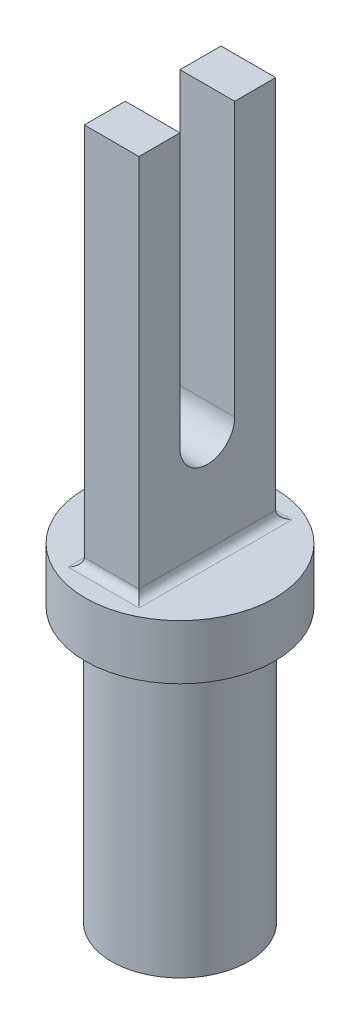
SolidWorks part; units mm, degrees
ref_plane "Front Plane" through (0, 0, 0) normal (0, 0, 1) x (1, 0, 0)
ref_plane "Top Plane" through (0, 0, 0) normal (0, 1, 0) x (1, 0, 0)
ref_plane "Right Plane" through (0, 0, 0) normal (1, 0, 0) x (0, 0, -1)
sketch "Sketch1" plane through (0, 0, 0) normal (0, 1, 0) x (1, 0, 0)
  circle A0 centre (0, 0) radius 17.325
  dimension "D1" = 34.65
extrude "Boss-Extrude1" add sketch "Sketch1" against normal blind 10
sketch "Sketch2" plane through (0, -10, 0) normal (0, -1, 0) x (1, 0, 0)
  circle A0 centre (0, 0) radius 12.5
  dimension "D1" = 25
extrude "Boss-Extrude2" add sketch "Sketch2" along normal blind 50
sketch "Sketch3" plane through (0, 0, 0) normal (0, 1, 0) x (1, 0, 0)
  line L0 (5, -12.5) -> (-5, 12.5) construction
  line L1 (5, -12.5) -> (-5, -12.5)
  line L2 (5, -12.5) -> (5, 12.5)
  line L3 (5, 12.5) -> (-5, 12.5)
  line L4 (-5, -12.5) -> (-5, 12.5)
  dimension "D1" = 10
  dimension "D2" = 25
extrude "Boss-Extrude3" add sketch "Sketch3" along normal blind 70
fillet "Fillet1" radius 1.5 4 edges at (0, 0, -12.5) (5, 0, 0) (0, 0, 12.5) (-5, 0, 0)
sketch "Sketch4" plane through (-5, 0, 0) normal (-1, 0, 0) x (0, 0, 1)
  line L0 (0, 70) -> (0, 20) construction
  line L1 (-12.5, 70) -> (12.5, 70) construction
  line L2 (-5, 20) -> (-5, 70)
  line L3 (-5, 70) -> (5, 70)
  line L4 (5, 70) -> (5, 20)
  circle A0 centre (0, 20) radius 5
  dimension "D1" = 10
  dimension "D2" = 50
extrude "Cut-Extrude1" cut sketch "Sketch4" against normal through all
